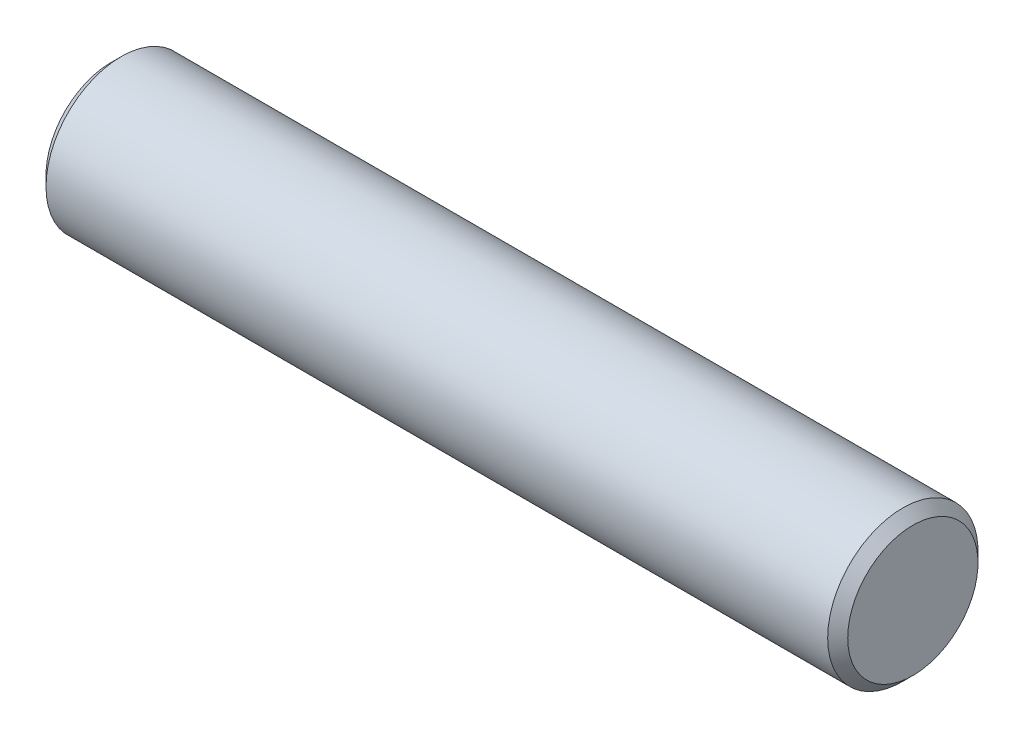
SolidWorks part; units mm, degrees
ref_plane "前视基准面" through (0, 0, 0) normal (0, 0, 1) x (1, 0, 0)
ref_plane "上视基准面" through (0, 0, 0) normal (0, 1, 0) x (1, 0, 0)
ref_plane "右视基准面" through (0, 0, 0) normal (1, 0, 0) x (0, 0, -1)
sketch "草图1" plane through (0, 0, 0) normal (0, 0, 1) x (1, 0, 0)
  line L0 (-6.3202, 0) -> (6.9944, 0) construction
  line L1 (-5.3427, 0) -> (-5.3427, 1.5)
  line L2 (-5.3427, 1.5) -> (10.6573, 1.5)
  line L3 (10.6573, 1.5) -> (10.6573, 0)
  line L4 (-5.3427, 0) -> (10.6573, 0)
  dimension "D1" = 16
  dimension "D2" = 1.5
revolve "旋转1" add sketch "草图1" angle 360 about L0
chamfer "倒角1" distance 0.2 angle 45 2 edges at (-5.3427, 0, 1.5) (10.6573, 0, 1.5)
